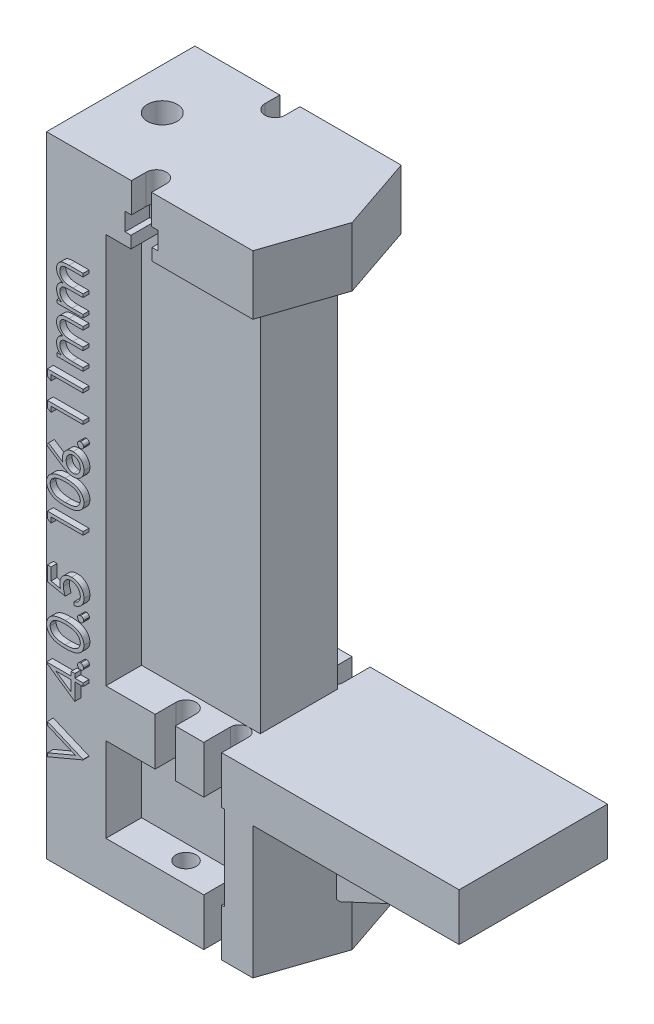
SolidWorks part; units mm, degrees
material "ABS"
ref_plane "Front" through (0, 0, 0) normal (0, 0, 1) x (1, 0, 0)
ref_plane "Top" through (0, 0, 0) normal (0, 1, 0) x (1, 0, 0)
ref_plane "Right" through (0, 0, 0) normal (1, 0, 0) x (0, 0, -1)
sketch "Sketch6" plane through (0, 0, 0) normal (0, 0, 1) x (1, 0, 0)
  line L0 (-25, 53.055) -> (15, 53.055)
  line L1 (15, 53.055) -> (15, 45.055)
  line L2 (15, 45.055) -> (-15, 45.055)
  line L3 (-15, 45.055) -> (-15, -45.055)
  line L4 (-15, -45.055) -> (25, -45.055)
  line L5 (25, -45.055) -> (25, -53.055)
  line L6 (25, -53.055) -> (-25, -53.055)
  line L7 (-25, -53.055) -> (-25, 53.055)
  line L8 (-25, 53.055) -> (25, -53.055) construction
  dimension "D1" = 106.11
  dimension "D2" = 8
  dimension "D3" = 10
  dimension "D4" = 50
  dimension "D5" = 40
extrude "Boss-Extrude2" add sketch "Sketch6" along normal mid plane 25
sketch "Sketch15" plane through (0, 0, 12.5) normal (0, 0, 1) x (1, 0, 0)
  line L0 (-15, -22.805) -> (15, -22.805)
  line L1 (-15, -45.055) -> (-15, 45.055) construction
  line L2 (-15, -30.805) -> (5, -30.805)
  line L3 (5, -53.055) -> (15, -53.055)
  line L4 (15, -53.055) -> (15, -22.805)
  line L5 (-25, -53.055) -> (25, -53.055) construction
  line L6 (-15, -30.805) -> (-15, -22.805)
  line L7 (5, -53.055) -> (5, -30.805)
  dimension "D2" = 8
extrude "Boss-Extrude3" add sketch "Sketch15" against normal up to surface (25 mm away) up to face at (0, 0, -12.5)
sketch "Sketch20" plane through (0, 53.055, 0) normal (0, 1, 0) x (1, 0, 0)
  line L0 (-10.7, 12.5) -> (-10.7, 10)
  line L1 (15, 12.5) -> (-25, 12.5) construction
  line L2 (-7.3, 10) -> (-7.3, 12.5)
  line L3 (-7.3, 12.5) -> (-10.7, 12.5)
  line L4 (0, 0) -> (15, 0) construction
  line L5 (15, -12.5) -> (15, 12.5) construction
  line L6 (-7.3, -12.5) -> (-10.7, -12.5)
  line L7 (-7.3, -10) -> (-7.3, -12.5)
  line L8 (-10.7, -12.5) -> (-10.7, -10)
  line L9 (-9, -10) -> (-9, 10) construction
  arc A0 (-10.7, 10) -> (-7.3, 10) centre (-9, 10) ccw
  arc A1 (-10.7, -10) -> (-7.3, -10) centre (-9, -10) cw
  dimension "D1" = 1.7
  dimension "D2" = 20
extrude "Cut-Extrude2" cut sketch "Sketch20" against normal up to next
sketch "Sketch21" plane through (0, -53.055, 0) normal (0, -1, 0) x (1, 0, 0)
  line L0 (-6.7, 12.5) -> (-6.7, 9)
  line L1 (-25, 12.5) -> (25, 12.5) construction
  line L2 (-3.3, 9) -> (-3.3, 12.5)
  line L3 (-3.3, 12.5) -> (-6.7, 12.5) construction
  line L4 (-5, -9) -> (-5, 9) construction
  line L5 (-6.7, 12.5) -> (-3.3, 12.5)
  line L7 (-3.3, -12.5) -> (-6.7, -12.5)
  line L8 (-3.3, -9) -> (-3.3, -12.5)
  line L9 (-6.7, -12.5) -> (-6.7, -9)
  arc A0 (-6.7, 9) -> (-3.3, 9) centre (-5, 9) ccw
  arc A1 (-6.7, -9) -> (-3.3, -9) centre (-5, -9) cw
  dimension "D1" = 1.7
  dimension "D2" = 18
extrude "Cut-Extrude3" cut sketch "Sketch21" against normal up to surface (30.25 mm away) up to face at (0, -22.805, 0)
sketch "Sketch22" plane through (0, 0, 0) normal (0, 0, 1) x (1, 0, 0)
  line L0 (-15, 21.805) -> (11, 45.055)
  line L1 (-7.3, 45.055) -> (15, 45.055) construction
  line L2 (-15, 45.055) -> (11, 45.055)
  line L5 (-15, -22.805) -> (-15, 45.055) construction
  line L7 (-15, 45.055) -> (-10.7, 45.055) construction
  line L8 (-15, 45.055) -> (-15, 21.805)
extrude "Boss-Extrude5" [suppressed] add sketch "Sketch22" along normal mid plane 4
sketch "Sketch23" plane through (0, 53.055, 0) normal (0, 1, 0) x (1, 0, 0)
  line L0 (-2.51, 12.5) -> (-2.51, 9)
  line L1 (15, 12.5) -> (-7.3, 12.5) construction
  line L2 (0.51, 9) -> (0.51, 12.5)
  line L3 (0.51, 12.5) -> (-2.51, 12.5)
  line L4 (-9, 10) -> (-1, 10) construction
  line L5 (-1, 10) -> (-1, 9) construction
  line L6 (0, 0) -> (12, 0) construction
  line L8 (0.51, -12.5) -> (-2.51, -12.5)
  line L9 (0.51, -9) -> (0.51, -12.5)
  line L10 (-2.51, -12.5) -> (-2.51, -9)
  line L11 (15, -12.5) -> (15, 12.5) construction
  arc A0 (-2.51, 9) -> (0.51, 9) centre (-1, 9) ccw
  arc A1 (-2.51, -9) -> (0.51, -9) centre (-1, -9) cw
  dimension "D1" = 1.51
  dimension "D2" = 8
  dimension "D3" = 1
  dimension "D4" = 3
extrude "Cut-Extrude4" [suppressed] cut sketch "Sketch23" against normal up to next
sketch "Sketch24" plane through (0, -53.055, 0) normal (0, -1, 0) x (1, 0, 0)
  line L0 (1.49, -12.5) -> (1.49, -8)
  line L1 (-3.3, -12.5) -> (25, -12.5) construction
  line L2 (4.51, -8) -> (4.51, -12.5)
  line L3 (4.51, -12.5) -> (1.49, -12.5)
  line L4 (3, -8) -> (3, -9) construction
  line L5 (3, -9) -> (-5, -9) construction
  line L9 (4.51, 12.5) -> (1.49, 12.5)
  line L10 (4.51, 8) -> (4.51, 12.5)
  line L11 (1.49, 12.5) -> (1.49, 8)
  arc A0 (1.49, -8) -> (4.51, -8) centre (3, -8) cw
  arc A1 (1.49, 8) -> (4.51, 8) centre (3, 8) ccw
  dimension "D2" = 8
  dimension "D3" = 1
extrude "Cut-Extrude6" cut sketch "Sketch24" against normal up to surface (30.25 mm away) up to face at (-3.3333, -22.805, 0)
sketch "Sketch28" plane through (0, 53.055, 0) normal (0, 1, 0) x (1, 0, 0)
  line L0 (-10.7, 10) -> (-7.3, 10) construction
  line L1 (-10.7, -10) -> (-7.3, -10) construction
  line L2 (-7.3, -12.5) -> (-7.3, -10) construction
  arc A0 (-10.7, 10) -> (-7.3, 10) centre (-9, 10) ccw construction
  arc A1 (-7.3, -10) -> (-10.7, -10) centre (-9, -10) ccw construction
sketch "Sketch29" plane through (-25, 0, 0) normal (-1, 0, 0) x (0, 0, 1)
  line L0 (-12.5, 53.055) -> (12.5, 53.055)
  line L1 (12.5, 53.055) -> (12.5, -53.055)
  line L2 (12.5, -53.055) -> (-12.9424, -53.055)
  line L3 (-12.9424, -53.055) -> (-12.5, 53.055)
extrude "Cut-Extrude7" [suppressed] cut sketch "Sketch29" against normal blind 6
sketch "Sketch30" plane through (0, -45.055, 0) normal (0, 1, 0) x (1, 0, 0)
  line L0 (25, 12.5) -> (25, -12.5)
  line L1 (25, -12.5) -> (15, -12.5)
  line L2 (15, -12.5) -> (15, 12.5)
  line L3 (15, 12.5) -> (25, 12.5)
extrude "Cut-Extrude8" cut sketch "Sketch30" against normal up to surface (8 mm away) up to face at (-0.8, -53.055, 0)
sketch "Sketch34" plane through (0, -22.805, 0) normal (0, 1, 0) x (1, 0, 0)
  line L1 (9.755, 12.5) -> (14, 0)
  line L2 (15, -12.5) -> (4.51, -12.5) construction
  line L3 (9.755, -12.5) -> (15, -12.5)
  line L6 (15, 12.5) -> (9.755, 12.5)
  line L7 (15, 12.5) -> (4.51, 12.5) construction
  line L9 (15, -12.5) -> (15, 12.5)
  line L10 (15, 0) -> (14, 0) construction
  line L11 (14, 0) -> (9.755, -12.5)
extrude "Cut-Extrude9" cut sketch "Sketch34" against normal through all both and the other way through all
sketch "Sketch35" plane through (0, 0, 12.5) normal (0, 0, 1) x (1, 0, 0)
  line L0 (-17.85, 53.055) -> (-17.85, -53.055) construction
  line L1 (-10.7, 53.055) -> (-25, 53.055) construction
  line L2 (-25, -53.055) -> (-6.7, -53.055) construction
  text T0 "V  4.0.5  106.11mm" font "Century Gothic" height 6
extrude "Boss-Extrude6" add sketch "Sketch35" along normal blind 1
sketch3d "3DSketch1"
  line L0 (4.51, -22.805, 12.5) -> (4.51, -30.805, 12.5)
  line L1 (4.51, -30.805, 12.5) -> (4.51, -30.805, -12.5)
  line L2 (4.51, -30.805, -12.5) -> (4.51, -22.805, -12.5)
  line L3 (4.51, -22.805, -12.5) -> (4.51, -22.805, 12.5)
extrude "Boss-Extrude7" add sketch "3DSketch1" along direction (1, 0, 0) on the side against the normal blind 40
sketch "Sketch37" plane through (0, 0, 0) normal (0, 0, 1) x (1, 0, 0)
  line L1 (14, -30.805) -> (44.51, -30.805)
  line L3 (5, -45.055) -> (14, -45.055) construction
  line L4 (14, -30.805) -> (14, -45.055)
  line L5 (14, -45.055) -> (44.51, -30.805)
extrude "Boss-Extrude17" add sketch "Sketch37" along direction (0, 0, 1) on the side of the normal mid plane 4 separate body
sketch "Sketch38" plane through (0, 45.055, 0) normal (0, -1, 0) x (1, 0, 0)
  line L0 (-11.75, 11.5877) -> (-11.75, 12.5) construction
  line L1 (-10.7, 10) -> (-7.3, 10) construction
  line L2 (-6.25, 8.4123) -> (-6.25, 11.5877) construction
  line L3 (-9, 6.8246) -> (-6.25, 8.4123)
  line L4 (-11.75, 8.4123) -> (-9, 6.8246)
  line L5 (-11.75, 11.5877) -> (-11.75, 8.4123) construction
  line L6 (-9, 13.1754) -> (-11.75, 11.5877) construction
  line L7 (-6.25, 11.5877) -> (-9, 13.1754) construction
  line L8 (-10.7, -10) -> (-7.3, -10) construction
  line L9 (-6.25, -11.5877) -> (-6.25, -8.4123) construction
  line L10 (-6.25, -8.4123) -> (-9, -6.8246)
  line L11 (-9, -6.8246) -> (-11.75, -8.4123)
  line L12 (-11.75, -8.4123) -> (-11.75, -11.5877) construction
  line L13 (-11.75, -11.5877) -> (-9, -13.1754) construction
  line L14 (-9, -13.1754) -> (-6.25, -11.5877) construction
  line L15 (-15, 12.5) -> (-10.7, 12.5) construction
  line L17 (-7.3, 12.5) -> (9.755, 12.5) construction
  line L18 (-6.25, 12.5) -> (-6.25, 11.5877) construction
  line L19 (-11.75, -11.5877) -> (-11.75, -12.5) construction
  line L20 (-15, -12.5) -> (-10.7, -12.5) construction
  line L21 (-11.77, -12.5) -> (-6.23, -12.5)
  line L22 (-7.3, -12.5) -> (9.755, -12.5) construction
  line L23 (-6.25, -12.5) -> (-6.25, -11.5877) construction
  line L24 (-11.77, 12.5) -> (-11.77, 8.4238)
  line L25 (-11.77, 8.4238) -> (-11.75, 8.4123)
  line L26 (-6.23, 12.5) -> (-6.23, 8.4238)
  line L27 (-6.23, 8.4238) -> (-6.25, 8.4123)
  line L28 (-11.77, 12.5) -> (-6.23, 12.5)
  line L29 (-6.25, -8.4123) -> (-6.23, -8.4238)
  line L30 (-6.23, -8.4238) -> (-6.23, -12.5)
  line L31 (-11.77, -12.5) -> (-11.77, -8.4238)
  line L32 (-11.77, -8.4238) -> (-11.75, -8.4123)
  circle A1 centre (-9, 10) radius 2.75 construction
  circle A2 centre (-9, 10) radius 3.1754 construction
  circle A3 centre (-9, -10) radius 3.1754 construction
  circle A4 centre (-9, -10) radius 2.75 construction
  point P18 (-6.25, -10)
  point P19 (-9, 10)
  point P24 (-7.625, -7.6184)
  point P25 (-10.375, -7.6184)
  dimension "D1" = 5.5
  dimension "D2" = 6
  dimension "D3" = 6.3509
  dimension "D4" = 5.5
  dimension "D5" = 6.3509
  dimension "D7" = 0.02
  dimension "D8" = 0.02
  dimension "D9" = 0.02
extrude "Cut-Extrude10" cut sketch "Sketch38" against normal blind 3
sketch "Sketch39" plane through (14, 0, 0) normal (-1, 0, 0) x (0, 0, 1)
  line L1 (-2, -45.055) -> (2, -45.055)
  line L2 (-2, -45.055) -> (-2, -30.805)
  line L3 (-2, -30.805) -> (2, -30.805)
  line L4 (2, -45.055) -> (2, -30.805)
extrude "Boss-Extrude18" add sketch "Sketch39" along normal blind 2.5
hole_wizard "Ø5.0mm Dowel Hole1" positions "Sketch41" profile "Sketch42" hole size "Ø5.0" standard "ANSI Metric"
sketch "Sketch41" plane through (0, 53.055, 0) normal (0, 1, 0) x (1, 0, 0)
  line L0 (-25, 0) -> (-18, 0) construction
  line L1 (-25, -12.5) -> (-25, 12.5) construction
  point P0 (-18, 0)
  dimension "D1" = 7
sketch "Sketch42" plane through (-18, 53.055, 0) normal (1, 0, 0) x (0, 0, 1)
  line L0 (0, 0) -> (0, 6.5022)
  line L1 (0, 6.5022) -> (2.5, 5)
  line L2 (2.5, 5) -> (2.5, 0)
  line L5 (2.5, 0) -> (0, 0)
  line L10 (0, 6.5022) -> (-2.5, 5) construction
  line L11 (0, -6.35) -> (0, 107.95) construction
  dimension "Hole Dia." = 5
  dimension "Hole Depth" = 5
  dimension "Drill Angle" = 118
sketch "Sketch43" plane through (0, 45.055, 0) normal (0, -1, 0) x (1, 0, 0)
  line L0 (-11.77, 12.5) -> (-10.77, 12.5)
  line L1 (-10.77, 12.5) -> (-10.77, 7.8465)
  line L2 (-6.23, 12.5) -> (-7.23, 12.5)
  line L3 (-7.23, 12.5) -> (-7.23, 7.8465)
  line L4 (-11.77, -12.5) -> (-10.77, -12.5)
  line L5 (-10.77, -12.5) -> (-10.77, -7.8465)
  line L6 (-6.23, -12.5) -> (-7.23, -12.5)
  line L7 (-7.23, -12.5) -> (-7.23, -7.8465)
  line L8 (5, 2) -> (5, -2)
  line L19 (-15, -12.5) -> (-11.77, -12.5)
  line L20 (-11.77, 8.4238) -> (-11.77, 12.5)
  line L21 (-11.77, -8.4238) -> (-9, -6.8246)
  line L22 (-9, -6.8246) -> (-6.23, -8.4238)
  line L23 (-11.77, 8.4238) -> (-11.77, 12.5)
  line L24 (-6.23, -12.5) -> (9.755, -12.5)
  line L25 (9.755, -12.5) -> (14, 0)
  line L26 (14, 0) -> (9.755, 12.5)
  line L27 (9.755, 12.5) -> (-6.23, 12.5)
  line L28 (-11.77, -12.5) -> (-11.77, -8.4238)
  line L29 (-6.23, 8.4238) -> (-9, 6.8246)
  line L30 (-9, 6.8246) -> (-11.77, 8.4238)
  line L31 (-11.77, -12.5) -> (-11.77, -8.4238)
  line L32 (-11.77, 12.5) -> (-15, 12.5)
  line L33 (-15, 12.5) -> (-15, -12.5)
  line L38 (-15, -12.5) -> (-11.77, -12.5)
  line L40 (-11.77, -8.4238) -> (-9, -6.8246)
  line L41 (-9, -6.8246) -> (-6.23, -8.4238)
  line L43 (-6.23, -12.5) -> (9.755, -12.5)
  line L44 (9.755, -12.5) -> (14, 0)
  line L45 (14, 0) -> (9.755, 12.5)
  line L46 (9.755, 12.5) -> (-6.23, 12.5)
  line L48 (-6.23, 8.4238) -> (-9, 6.8246)
  line L49 (-9, 6.8246) -> (-11.77, 8.4238)
  line L51 (-11.77, 12.5) -> (-15, 12.5)
  line L52 (-15, 12.5) -> (-15, -12.5)
  line L57 (-6.23, -8.4238) -> (-6.23, -12.5)
  line L58 (-6.23, -8.4238) -> (-6.23, -12.5)
  line L59 (-6.23, 12.5) -> (-6.23, 8.4238)
  line L60 (-6.23, 12.5) -> (-6.23, 8.4238)
  dimension "D2" = 1
  dimension "D3" = 1
  dimension "D4" = 1
  dimension "D5" = 1
  dimension "D1" = 0
extrude "Boss-Extrude19" add sketch "Sketch43" along normal blind 2
sketch "Sketch44" plane through (0, -53.055, 0) normal (0, -1, 0) x (1, 0, 0)
  line L0 (-6.7, -9) -> (-6.7, -12.5)
  line L1 (-6.7, -12.5) -> (-3.3, -12.5)
  line L2 (-3.3, -12.5) -> (-3.3, -9)
  line L3 (-6.7, 9) -> (-6.7, 12.5)
  line L4 (-6.7, 12.5) -> (-3.3, 12.5)
  line L5 (-3.3, 12.5) -> (-3.3, 9)
  circle A0 centre (-5, -9) radius 1.7
  circle A1 centre (-5, 9) radius 1.7
  line M8 (-3.3, 12.5) -> (-3.3, 9)
  line M10 (-6.7, 9) -> (-6.7, 12.5)
  line M14 (-6.7, -12.5) -> (-6.7, -9)
  line M16 (-3.3, -9) -> (-3.3, -12.5)
extrude "Boss-Extrude20" add sketch "Sketch44" against normal up to surface (8 mm away) contours A1 L4 M8 M10 | A0 L1 M14 M16
sketch "Sketch45" plane through (0, -22.805, 0) normal (0, 1, 0) x (1, 0, 0)
  line L0 (-15, 12.5) -> (-15, -12.5) construction
  line L1 (-15, -6.49) -> (5, -6.49)
  line L2 (-15, -6.49) -> (-15, 6.49)
  line L3 (-15, 6.49) -> (5, 6.49)
  line L4 (5, -6.49) -> (5, 6.49)
  line L5 (5, -6.49) -> (5, 6.49) construction
  line L7 (5, -12.5) -> (5, 12.5) construction
  arc A0 (1.49, 8) -> (4.51, 8) centre (3, 8) ccw construction
  arc A1 (4.51, -8) -> (1.49, -8) centre (3, -8) ccw construction
extrude "Boss-Extrude21" add sketch "Sketch45" along normal up to next and the other way up to surface
